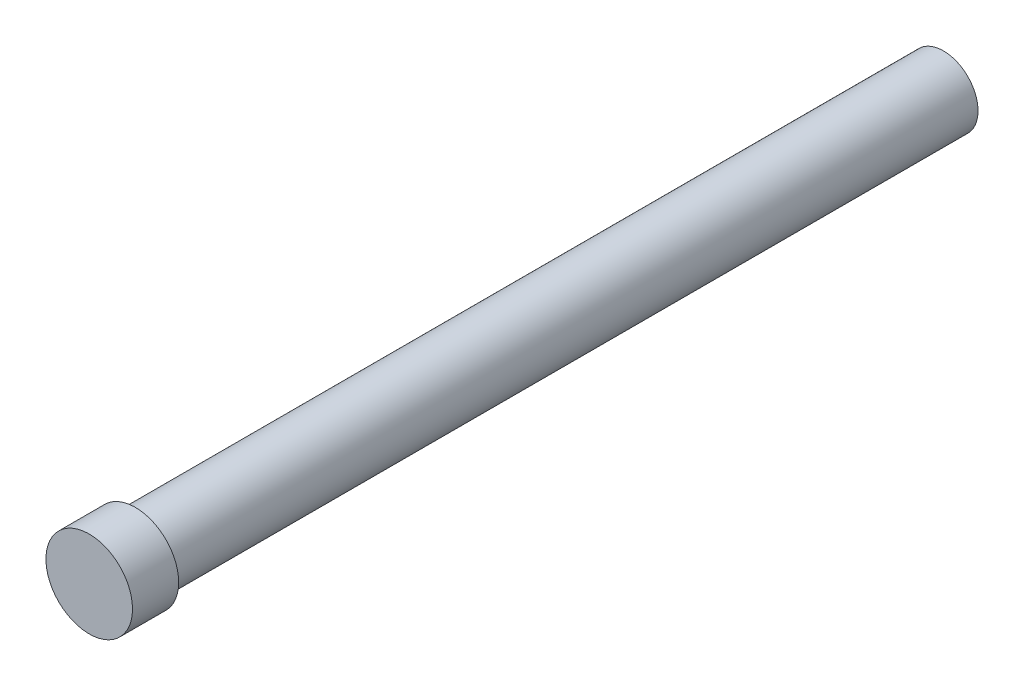
SolidWorks part; units mm, degrees
ref_plane "Front Plane" through (0, 0, 0) normal (0, 0, 1) x (1, 0, 0)
ref_plane "Top Plane" through (0, 0, 0) normal (0, 1, 0) x (1, 0, 0)
ref_plane "Right Plane" through (0, 0, 0) normal (1, 0, 0) x (0, 0, -1)
sketch "Sketch1" plane through (0, 0, 0) normal (0, 0, 1) x (1, 0, 0)
  circle A0 centre (0, 0) radius 7.5
  dimension "D1" = 15
extrude "Boss-Extrude1" add sketch "Sketch1" along normal blind 8
sketch "Sketch3" plane through (0, 0, 0) normal (0, 0, -1) x (-1, 0, 0)
  circle A0 centre (0, 0) radius 6
  dimension "D1" = 12
extrude "Boss-Extrude2" add sketch "Sketch3" along normal blind 140
